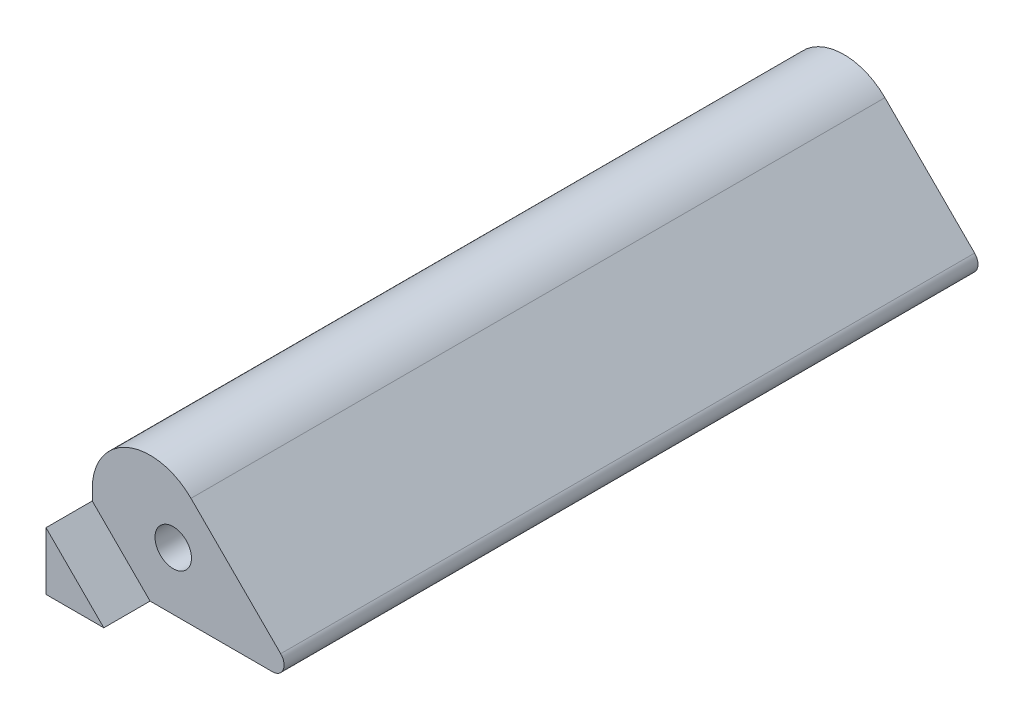
SolidWorks part; units mm, degrees
ref_plane "Plano frontal" through (0, 0, 0) normal (0, 0, 1) x (1, 0, 0)
ref_plane "Plano superior" through (0, 0, 0) normal (0, 1, 0) x (1, 0, 0)
ref_plane "Plano direito" through (0, 0, 0) normal (1, 0, 0) x (0, 0, -1)
sketch "Esboço1" plane through (0, 0, 0) normal (0, 0, 1) x (1, 0, 0)
  line L0 (0, 0) -> (18, 0)
  line L1 (18, 0) -> (0, 18)
  line L2 (0, 18) -> (0, 0)
  dimension "D1" = 18
  dimension "D2" = 45
extrude "Ressalto-extrusão1" add sketch "Esboço1" along normal blind 60
sketch "Esboço2" plane through (0, 0, 60) normal (0, 0, 1) x (1, 0, 0)
  line L0 (0, 0) -> (0, 5)
  line L1 (0, 18) -> (0, 0) construction
  line L2 (0, 5) -> (5, 0)
  line L3 (0, 0) -> (18, 0) construction
  line L4 (5, 0) -> (0, 0)
  dimension "D1" = 5
  dimension "D2" = 5
extrude "Ressalto-extrusão2" add sketch "Esboço2" along normal blind 4
sketch "Esboço3" plane through (0, 0, 0) normal (0, 0, -1) x (-1, 0, 0)
  line L0 (0, 0) -> (0, 5)
  line L1 (0, 18) -> (0, 0) construction
  line L2 (0, 5) -> (-5, 0)
  line L3 (0, 0) -> (-18, 0) construction
  line L4 (-5, 0) -> (0, 0)
  dimension "D1" = 5
  dimension "D2" = 5
extrude "Ressalto-extrusão3" add sketch "Esboço3" along normal blind 4
hole_wizard "Furo roscado para conduíte de M3x0.51" positions "Esboço4" profile "Esboço6" tap size "M3x0.5" standard "Helicoil® Metric"
sketch "Esboço4" plane through (0, 0, 60) normal (0, 0, 1) x (1, 0, 0)
  line L0 (0, 18) -> (0, 5) construction
  line L1 (5, 0) -> (18, 0) construction
  point P0 (7, 5)
  dimension "D1" = 7
  dimension "D2" = 5
sketch "Esboço6" plane through (7, 5, 60) normal (1, 0, 0) x (0, -1, 0)
  line L0 (0, 0) -> (0, 10.9464)
  line L1 (0, 10.9464) -> (1.575, 10)
  line L2 (1.575, 10) -> (1.575, 0)
  line L5 (1.575, 0) -> (0, 0)
  line L10 (0, 10.9464) -> (-1.575, 10) construction
  line L11 (0, -6.35) -> (0, 107.95) construction
  dimension "Tap Drill Dia." = 3.15
  dimension "Tap Drill Depth" = 10
  dimension "Drill Angle" = 118
cosmetic thread "Rosca de furo1" parameters "D1"=10, "D2"=3.716
hole_wizard "Furo roscado para conduíte de M3x0.52" positions "Esboço7" profile "Esboço8" tap size "M3x0.5" standard "Helicoil® Metric"
sketch "Esboço7" plane through (0, 0, 0) normal (0, 0, -1) x (-1, 0, 0)
  line L0 (0, 18) -> (0, 5) construction
  line L1 (-5, 0) -> (-18, 0) construction
  point P0 (-7, 5)
  dimension "D1" = 7
  dimension "D2" = 5
sketch "Esboço8" plane through (7, 5, 0) normal (1, 0, 0) x (0, 1, 0)
  line L0 (0, 0) -> (0, 8.4464)
  line L1 (0, 8.4464) -> (1.575, 7.5)
  line L2 (1.575, 7.5) -> (1.575, 0)
  line L5 (1.575, 0) -> (0, 0)
  line L10 (0, 8.4464) -> (-1.575, 7.5) construction
  line L11 (0, -6.35) -> (0, 107.95) construction
  dimension "Tap Drill Dia." = 3.15
  dimension "Tap Drill Depth" = 7.5
  dimension "Drill Angle" = 118
cosmetic thread "Rosca de furo2"
fillet "Filete1" radius 1 1 edges at (18, 0, 30)
fillet "Filete2" radius 5 1 edges at (0, 18, 30)
